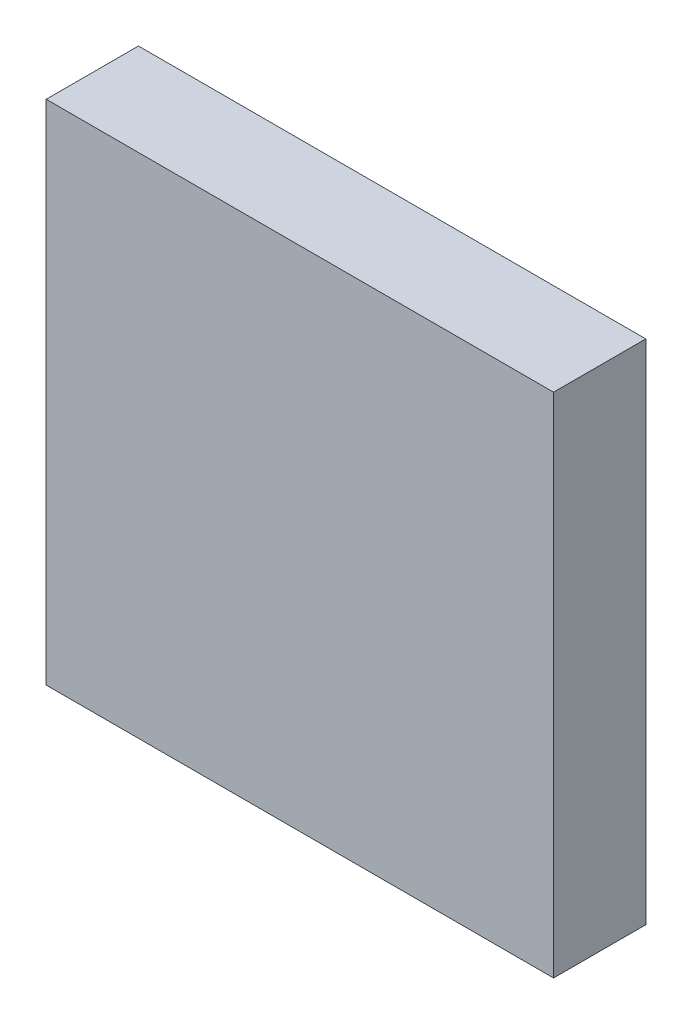
SolidWorks part; units mm, degrees
ref_plane "Front Plane" through (0, 0, 0) normal (0, 0, 1) x (1, 0, 0)
ref_plane "Top Plane" through (0, 0, 0) normal (0, 1, 0) x (1, 0, 0)
ref_plane "Right Plane" through (0, 0, 0) normal (1, 0, 0) x (0, 0, -1)
sketch "Sketch1" plane through (0, 0, 0) normal (0, 1, 0) x (1, 0, 0)
  line L1 (-69.85, 12.7) -> (69.85, 12.7)
  line L2 (-69.85, 12.7) -> (-69.85, -12.7)
  line L3 (-69.85, -12.7) -> (69.85, -12.7)
  line L4 (69.85, 12.7) -> (69.85, -12.7)
  point P7 (9.7622, -2.1881)
  dimension "D1" = 139.7
  dimension "D2" = 25.4
  dimension "D3" = 69.85
  dimension "D4" = 12.7
extrude "Boss-Extrude1" add sketch "Sketch1" along normal blind 139.7
